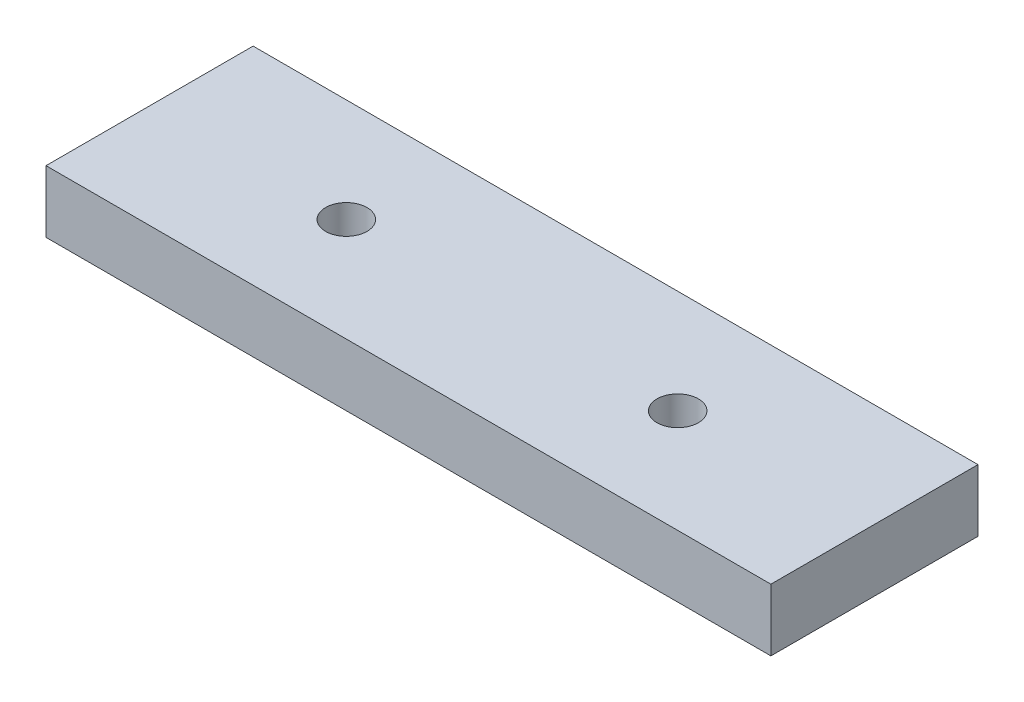
SolidWorks part; units mm, degrees
ref_plane "Front Plane" through (0, 0, 0) normal (0, 0, 1) x (1, 0, 0)
ref_plane "Top Plane" through (0, 0, 0) normal (0, 1, 0) x (1, 0, 0)
ref_plane "Right Plane" through (0, 0, 0) normal (1, 0, 0) x (0, 0, -1)
sketch "Sketch1" plane through (0, 0, 0) normal (0, 1, 0) x (1, 0, 0)
  line L1 (-17.5, -5) -> (17.5, -5)
  line L2 (-17.5, -5) -> (-17.5, 5)
  line L3 (-17.5, 5) -> (17.5, 5)
  line L4 (17.5, -5) -> (17.5, 5)
  line L5 (-17.5, -5) -> (17.5, 5) construction
  line L6 (-17.5, 5) -> (17.5, -5) construction
  point P0 (0, 0)
  dimension "D1" = 35
  dimension "D2" = 10
extrude "Boss-Extrude1" add sketch "Sketch1" along normal mid plane 3
sketch "Sketch2" plane through (0, 1.5, 0) normal (0, 1, 0) x (1, 0, 0)
  circle A0 centre (-8, 0) radius 1
  circle A1 centre (8, 0) radius 1
  dimension "D1" = 2
  dimension "D2" = 2
  dimension "D3" = 8
  dimension "D4" = 8
extrude "Cut-Extrude1" cut sketch "Sketch2" against normal through all
